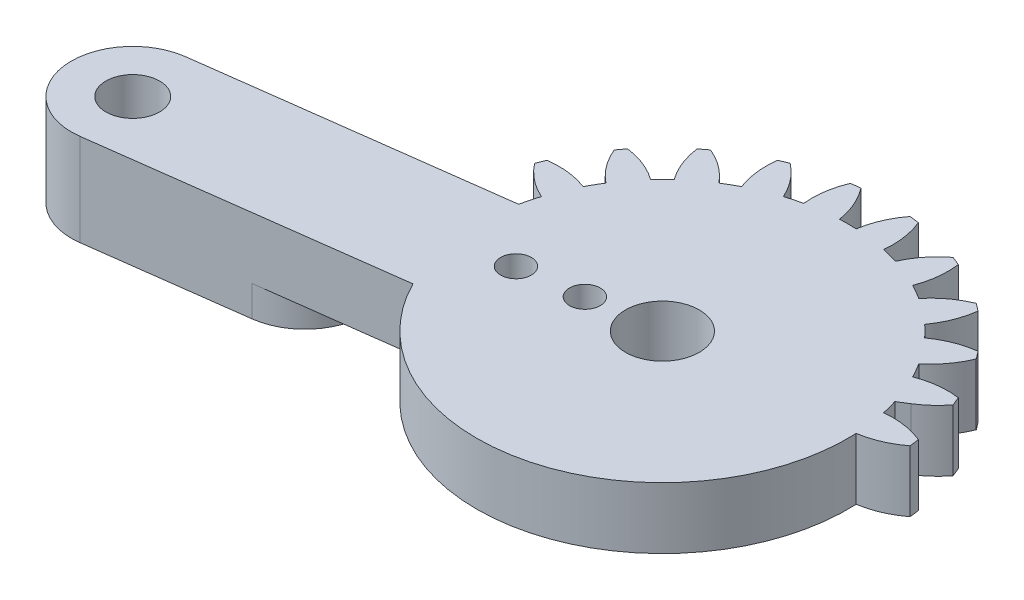
SolidWorks part; units mm, degrees
ref_plane "Front Plane" through (0, 0, 0) normal (0, 0, 1) x (1, 0, 0)
ref_plane "Top Plane" through (0, 0, 0) normal (0, 1, 0) x (1, 0, 0)
ref_plane "Right Plane" through (0, 0, 0) normal (1, 0, 0) x (0, 0, -1)
sketch "Sketch1" plane through (0, 0, 0) normal (0, 1, 0) x (1, 0, 0)
  line L0 (20.6437, 4) -> (2.0816, 4)
  line L1 (2.0816, -4) -> (20.6437, -4)
  arc A0 (2.0816, 4) -> (3.5217, 5.3071) centre (-0.7683, 8.5867) ccw
  arc A1 (3.5217, 5.3071) -> (3.2829, 5.8838) centre (-10.1063, 0) ccw
  arc A2 (3.2829, 5.8838) -> (0.6271, 5.5703) centre (2.5684, 0.5313) ccw
  arc A3 (0.6271, 5.5703) -> (0.0844, 6.5103) centre (-10.1063, 0) ccw
  arc A4 (0.0844, 6.5103) -> (1.6838, 8.6535) centre (-3.3089, 10.711) ccw
  arc A5 (1.6838, 8.6535) -> (1.3038, 9.1487) centre (-10.1063, 0) ccw
  arc A6 (1.3038, 9.1487) -> (-1.1803, 8.1585) centre (1.999, 3.7936) ccw
  arc A7 (-1.1803, 8.1585) -> (-1.9479, 8.926) centre (-10.1063, 0) ccw
  arc A8 (-1.9479, 8.926) -> (-0.9576, 11.4102) centre (-6.3127, 12.1053) ccw
  arc A9 (-0.9576, 11.4102) -> (-1.4528, 11.7901) centre (-10.1063, 0) ccw
  arc A10 (-1.4528, 11.7901) -> (-3.596, 10.1907) centre (0.6046, 6.7975) ccw
  arc A11 (-3.596, 10.1907) -> (-4.5361, 10.7334) centre (-10.1063, 0) ccw
  arc A12 (-4.5361, 10.7334) -> (-4.2225, 13.3892) centre (-9.5751, 12.6747) ccw
  arc A13 (-4.2225, 13.3892) -> (-4.7992, 13.6281) centre (-10.1063, 0) ccw
  arc A14 (-4.7992, 13.6281) -> (-6.4554, 11.5285) centre (-1.5196, 9.3381) ccw
  arc A15 (-6.4554, 11.5285) -> (-7.5039, 11.8094) centre (-10.1063, 0) ccw
  arc A16 (-7.5039, 11.8094) -> (-7.8884, 14.4558) centre (-12.8736, 12.3803) ccw
  arc A17 (-7.8884, 14.4558) -> (-8.5072, 14.5373) centre (-10.1063, 0) ccw
  arc A18 (-8.5072, 14.5373) -> (-9.5636, 12.0806) centre (-4.2291, 11.2423) ccw
  arc A19 (-9.5636, 12.0806) -> (-10.6491, 12.0806) centre (-10.1063, 0) ccw
  arc A20 (-10.6491, 12.0806) -> (-11.7054, 14.5373) centre (-15.9836, 11.2423) ccw
  arc A21 (-11.7054, 14.5373) -> (-12.3243, 14.4558) centre (-10.1063, 0) ccw
  arc A22 (-12.3243, 14.4558) -> (-12.7088, 11.8094) centre (-7.3391, 12.3803) ccw
  arc A23 (-12.7088, 11.8094) -> (-13.7573, 11.5285) centre (-10.1063, 0) ccw
  arc A24 (-13.7573, 11.5285) -> (-15.4135, 13.6281) centre (-18.6931, 9.3381) ccw
  arc A25 (-15.4135, 13.6281) -> (-15.9901, 13.3892) centre (-10.1063, 0) ccw
  arc A26 (-15.9901, 13.3892) -> (-15.6766, 10.7334) centre (-10.6376, 12.6747) ccw
  arc A27 (-15.6766, 10.7334) -> (-16.6166, 10.1907) centre (-10.1063, 0) ccw
  arc A28 (-16.6166, 10.1907) -> (-18.7599, 11.7901) centre (-20.8173, 6.7975) ccw
  arc A29 (-18.7599, 11.7901) -> (-19.255, 11.4102) centre (-10.1063, 0) ccw
  arc A30 (-19.255, 11.4102) -> (-18.2648, 8.926) centre (-13.9, 12.1053) ccw
  arc A31 (-18.2648, 8.926) -> (-19.0324, 8.1585) centre (-10.1063, 0) ccw
  arc A32 (-19.0324, 8.1585) -> (-21.5165, 9.1487) centre (-22.2117, 3.7936) ccw
  arc A33 (-21.5165, 9.1487) -> (-21.8965, 8.6535) centre (-10.1063, 0) ccw
  arc A34 (-21.8965, 8.6535) -> (-20.2971, 6.5103) centre (-16.9038, 10.711) ccw
  arc A35 (-20.2971, 6.5103) -> (-20.8398, 5.5703) centre (-10.1063, 0) ccw
  arc A36 (-20.8398, 5.5703) -> (-23.4956, 5.8838) centre (-22.7811, 0.5313) ccw
  arc A37 (-23.4956, 5.8838) -> (-23.7344, 5.3071) centre (-10.1063, 0) ccw
  arc A38 (-23.7344, 5.3071) -> (-21.6348, 3.6509) centre (-19.4444, 8.5867) ccw
  arc A39 (-21.6348, 3.6509) -> (-21.9157, 2.6025) centre (-10.1063, 0) ccw
  arc A40 (-21.9157, 2.6025) -> (-24.5622, 2.2179) centre (-22.4867, -2.7673) ccw
  arc A41 (-24.5622, 2.2179) -> (-24.6437, 1.5991) centre (-10.1063, 0) ccw
  arc A42 (-24.6437, 1.5991) -> (-22.1869, 0.5427) centre (-21.3486, 5.8773) ccw
  arc A43 (-22.1869, 0.5427) -> (-22.1869, -0.5427) centre (-10.1063, 0) ccw
  arc A44 (-22.1869, -0.5427) -> (-24.6437, -1.5991) centre (-21.3486, -5.8773) ccw
  arc A45 (-24.6437, -1.5991) -> (-24.5622, -2.2179) centre (-10.1063, 0) ccw
  arc A46 (-24.5622, -2.2179) -> (-21.9157, -2.6025) centre (-22.4867, 2.7673) ccw
  arc A47 (-21.9157, -2.6025) -> (-21.6348, -3.6509) centre (-10.1063, 0) ccw
  arc A48 (-21.6348, -3.6509) -> (-23.7344, -5.3071) centre (-19.4444, -8.5867) ccw
  arc A49 (-23.7344, -5.3071) -> (-23.4956, -5.8838) centre (-10.1063, 0) ccw
  arc A50 (-23.4956, -5.8838) -> (-20.8398, -5.5703) centre (-22.7811, -0.5313) ccw
  arc A51 (-20.8398, -5.5703) -> (-20.2971, -6.5103) centre (-10.1063, 0) ccw
  arc A52 (-20.2971, -6.5103) -> (-21.8965, -8.6535) centre (-16.9038, -10.711) ccw
  arc A53 (-21.8965, -8.6535) -> (-21.5165, -9.1487) centre (-10.1063, 0) ccw
  arc A54 (-21.5165, -9.1487) -> (-19.0324, -8.1585) centre (-22.2117, -3.7936) ccw
  arc A55 (-19.0324, -8.1585) -> (-18.2648, -8.926) centre (-10.1063, 0) ccw
  arc A56 (-18.2648, -8.926) -> (-19.255, -11.4102) centre (-13.9, -12.1053) ccw
  arc A57 (-19.255, -11.4102) -> (-18.7599, -11.7901) centre (-10.1063, 0) ccw
  arc A58 (-18.7599, -11.7901) -> (-16.6166, -10.1907) centre (-20.8173, -6.7975) ccw
  arc A59 (-16.6166, -10.1907) -> (-15.6766, -10.7334) centre (-10.1063, 0) ccw
  arc A60 (-15.6766, -10.7334) -> (-15.9901, -13.3892) centre (-10.6376, -12.6747) ccw
  arc A61 (-15.9901, -13.3892) -> (-15.4135, -13.6281) centre (-10.1063, 0) ccw
  arc A62 (-15.4135, -13.6281) -> (-13.7573, -11.5285) centre (-18.6931, -9.3381) ccw
  arc A63 (-13.7573, -11.5285) -> (-12.7088, -11.8094) centre (-10.1063, 0) ccw
  arc A64 (-12.7088, -11.8094) -> (-12.3243, -14.4558) centre (-7.3391, -12.3803) ccw
  arc A65 (-12.3243, -14.4558) -> (-11.7054, -14.5373) centre (-10.1063, 0) ccw
  arc A66 (-11.7054, -14.5373) -> (-10.6491, -12.0806) centre (-15.9836, -11.2423) ccw
  arc A67 (-10.6491, -12.0806) -> (-9.5636, -12.0806) centre (-10.1063, 0) ccw
  arc A68 (-9.5636, -12.0806) -> (-8.5072, -14.5373) centre (-4.2291, -11.2423) ccw
  arc A69 (-8.5072, -14.5373) -> (-7.8884, -14.4558) centre (-10.1063, 0) ccw
  arc A70 (-7.8884, -14.4558) -> (-7.5039, -11.8094) centre (-12.8736, -12.3803) ccw
  arc A71 (-7.5039, -11.8094) -> (-6.4554, -11.5285) centre (-10.1063, 0) ccw
  arc A72 (-6.4554, -11.5285) -> (-4.7992, -13.6281) centre (-1.5196, -9.3381) ccw
  arc A73 (-4.7992, -13.6281) -> (-4.2225, -13.3892) centre (-10.1063, 0) ccw
  arc A74 (-4.2225, -13.3892) -> (-4.5361, -10.7334) centre (-9.5751, -12.6747) ccw
  arc A75 (-4.5361, -10.7334) -> (-3.596, -10.1907) centre (-10.1063, 0) ccw
  arc A76 (-3.596, -10.1907) -> (-1.4528, -11.7901) centre (0.6046, -6.7975) ccw
  arc A77 (-1.4528, -11.7901) -> (-0.9576, -11.4102) centre (-10.1063, 0) ccw
  arc A78 (-0.9576, -11.4102) -> (-1.9479, -8.926) centre (-6.3127, -12.1053) ccw
  arc A79 (-1.9479, -8.926) -> (-1.1803, -8.1585) centre (-10.1063, 0) ccw
  arc A80 (-1.1803, -8.1585) -> (1.3038, -9.1487) centre (1.999, -3.7936) ccw
  arc A81 (1.3038, -9.1487) -> (1.6838, -8.6535) centre (-10.1063, 0) ccw
  arc A82 (1.6838, -8.6535) -> (0.0844, -6.5103) centre (-3.3089, -10.711) ccw
  arc A83 (0.0844, -6.5103) -> (0.6271, -5.5703) centre (-10.1063, 0) ccw
  arc A84 (0.6271, -5.5703) -> (3.2829, -5.8838) centre (2.5684, -0.5313) ccw
  arc A85 (3.2829, -5.8838) -> (3.5217, -5.3071) centre (-10.1063, 0) ccw
  arc A86 (3.5217, -5.3071) -> (2.0816, -4) centre (-0.7683, -8.5867) ccw
  arc A87 (20.6437, -4) -> (20.6437, 4) centre (20.6437, 0) ccw
  circle A88 centre (-10.1063, 0) radius 1.5
  circle A89 centre (20.6437, 0) radius 1.5
  dimension "D1" = 3
  dimension "D2" = 3
extrude "Boss-Extrude1" add sketch "Sketch1" along normal blind 4
sketch "Sketch3" plane through (0, 4, 0) normal (0, 1, 0) x (1, 0, 0)
  line L0 (-10.1063, 0) -> (-40.8563, 0) construction
  line L1 (-10.1063, 0) -> (-40.5933, -4.0137)
  line L2 (-10.6284, 3.9658) -> (-41.1154, -0.0479)
  line L3 (-9.5842, -3.9658) -> (-40.0712, -7.9795)
  line L4 (-10.1063, 0) -> (-4.5096, 13.5117) construction
  line L5 (-10.1063, 0) -> (-8.1974, 14.4999) construction
  circle A0 centre (-10.1063, 0) radius 1.5
  circle A1 centre (20.6437, 0) radius 1.5 construction
  circle A2 centre (20.6437, 0) radius 1.5
  circle A3 centre (-40.5933, -4.0137) radius 1.75
  circle A4 centre (-40.5933, -4.0137) radius 4
  circle A5 centre (-10.1063, 0) radius 4
  arc A6 (-4.2225, 13.3892) -> (-4.7992, 13.6281) centre (-10.1063, 0) ccw construction
  arc A7 (-7.8884, 14.4558) -> (-8.5072, 14.5373) centre (-10.1063, 0) ccw construction
  dimension "D2" = 3
  dimension "D5" = 3.5
  dimension "D6" = 8
  dimension "D7" = 8
  dimension "D1" = 30.75
  dimension "D4" = 7.5
extrude "Boss-Extrude2" add sketch "Sketch3" against normal blind 4
sketch "Sketch4" plane through (0, 4, 0) normal (0, 1, 0) x (1, 0, 0)
  line L0 (20.6437, 4) -> (2.0816, 4) construction
  line L1 (2.0816, -4) -> (20.6437, -4) construction
  line L2 (20.6437, 4) -> (2.0816, 4)
  line L3 (2.0816, -4) -> (20.6437, -4)
  line L4 (2.0816, 4) -> (1.4381, 3.6001)
  line L5 (-21.6245, -5.5509) -> (-20.8986, -5.4553)
  line L6 (-10.1063, 0) -> (0.0844, 6.5103) construction
  line L7 (-10.1063, 0) -> (1.9742, 0.5427) construction
  line L8 (-24.5755, 2.1296) -> (-41.1154, -0.0479)
  line L9 (-40.0712, -7.9795) -> (-23.5312, -5.8019)
  line L10 (2.0816, -4) -> (20.6437, -4)
  line L11 (20.6437, 4) -> (2.0816, 4)
  line L12 (-21.9429, 2.4762) -> (-41.1154, -0.0479)
  line L13 (-40.0712, -7.9795) -> (-21.6245, -5.5509)
  line L14 (2.0816, -4) -> (20.6437, -4)
  line L15 (20.6437, 4) -> (2.0816, 4)
  circle A0 centre (-10.1063, 0) radius 12.0927
  arc A1 (3.2829, 5.8838) -> (0.6271, 5.5703) centre (2.5684, 0.5313) ccw construction
  arc A2 (3.5217, 5.3071) -> (3.2829, 5.8838) centre (-10.1063, 0) ccw construction
  arc A3 (2.0816, 4) -> (3.5217, 5.3071) centre (-0.7683, 8.5867) ccw construction
  arc A4 (20.6437, -4) -> (20.6437, 4) centre (20.6437, 0) ccw construction
  arc A5 (3.5217, -5.3071) -> (2.0816, -4) centre (-0.7683, -8.5867) ccw construction
  arc A6 (3.2829, -5.8838) -> (3.5217, -5.3071) centre (-10.1063, 0) ccw construction
  arc A7 (0.6271, -5.5703) -> (3.2829, -5.8838) centre (2.5684, -0.5313) ccw construction
  arc A8 (3.2829, 5.8838) -> (0.6271, 5.5703) centre (2.5684, 0.5313) ccw
  arc A9 (3.5217, 5.3071) -> (3.2829, 5.8838) centre (-10.1063, 0) ccw
  arc A10 (2.0816, 4) -> (3.5217, 5.3071) centre (-0.7683, 8.5867) ccw
  arc A11 (20.6437, -4) -> (20.6437, 4) centre (20.6437, 0) ccw
  arc A12 (3.5217, -5.3071) -> (2.0816, -4) centre (-0.7683, -8.5867) ccw
  arc A13 (3.2829, -5.8838) -> (3.5217, -5.3071) centre (-10.1063, 0) ccw
  arc A14 (0.6271, -5.5703) -> (3.2829, -5.8838) centre (2.5684, -0.5313) ccw
  arc A15 (1.9742, 0.5427) -> (4.431, 1.5991) centre (1.1359, 5.8773) ccw
  arc A16 (4.3495, 2.2179) -> (1.7031, 2.6025) centre (2.274, -2.7673) ccw
  arc A17 (4.431, 1.5991) -> (4.3495, 2.2179) centre (-10.1063, 0) ccw
  arc A95 (-21.6348, 3.6509) -> (-21.9157, 2.6025) centre (-10.1063, 0) ccw
  arc A96 (-41.1154, -0.0479) -> (-40.0712, -7.9795) centre (-40.5933, -4.0137) ccw
  arc A97 (-20.2971, -6.5103) -> (-21.8965, -8.6535) centre (-16.9038, -10.711) ccw
  arc A98 (-21.8965, -8.6535) -> (-21.5165, -9.1487) centre (-10.1063, 0) ccw
  arc A99 (-21.5165, -9.1487) -> (-19.0324, -8.1585) centre (-22.2117, -3.7936) ccw
  arc A100 (-19.0324, -8.1585) -> (-18.2648, -8.926) centre (-10.1063, 0) ccw
  arc A101 (-18.2648, -8.926) -> (-19.255, -11.4102) centre (-13.9, -12.1053) ccw
  arc A102 (-19.255, -11.4102) -> (-18.7599, -11.7901) centre (-10.1063, 0) ccw
  arc A103 (-18.7599, -11.7901) -> (-16.6166, -10.1907) centre (-20.8173, -6.7975) ccw
  arc A104 (-16.6166, -10.1907) -> (-15.6766, -10.7334) centre (-10.1063, 0) ccw
  arc A105 (-15.6766, -10.7334) -> (-15.9901, -13.3892) centre (-10.6376, -12.6747) ccw
  arc A106 (-15.9901, -13.3892) -> (-15.4135, -13.6281) centre (-10.1063, 0) ccw
  arc A107 (-15.4135, -13.6281) -> (-13.7573, -11.5285) centre (-18.6931, -9.3381) ccw
  arc A108 (-13.7573, -11.5285) -> (-12.7088, -11.8094) centre (-10.1063, 0) ccw
  arc A109 (-12.7088, -11.8094) -> (-12.3243, -14.4558) centre (-7.3391, -12.3803) ccw
  arc A110 (-12.3243, -14.4558) -> (-11.7054, -14.5373) centre (-10.1063, 0) ccw
  arc A111 (-11.7054, -14.5373) -> (-10.6491, -12.0806) centre (-15.9836, -11.2423) ccw
  arc A112 (-10.6491, -12.0806) -> (-9.5636, -12.0806) centre (-10.1063, 0) ccw
  arc A113 (-9.5636, -12.0806) -> (-8.5072, -14.5373) centre (-4.2291, -11.2423) ccw
  arc A114 (-8.5072, -14.5373) -> (-7.8884, -14.4558) centre (-10.1063, 0) ccw
  arc A115 (-7.8884, -14.4558) -> (-7.5039, -11.8094) centre (-12.8736, -12.3803) ccw
  arc A116 (-7.5039, -11.8094) -> (-6.4554, -11.5285) centre (-10.1063, 0) ccw
  arc A117 (-6.4554, -11.5285) -> (-4.7992, -13.6281) centre (-1.5196, -9.3381) ccw
  arc A118 (-4.7992, -13.6281) -> (-4.2225, -13.3892) centre (-10.1063, 0) ccw
  arc A119 (-4.2225, -13.3892) -> (-4.5361, -10.7334) centre (-9.5751, -12.6747) ccw
  arc A120 (-4.5361, -10.7334) -> (-3.596, -10.1907) centre (-10.1063, 0) ccw
  arc A121 (-3.596, -10.1907) -> (-1.4528, -11.7901) centre (0.6046, -6.7975) ccw
  arc A122 (-1.4528, -11.7901) -> (-0.9576, -11.4102) centre (-10.1063, 0) ccw
  arc A123 (-0.9576, -11.4102) -> (-1.9479, -8.926) centre (-6.3127, -12.1053) ccw
  arc A124 (-1.9479, -8.926) -> (-1.1803, -8.1585) centre (-10.1063, 0) ccw
  arc A125 (-1.1803, -8.1585) -> (1.3038, -9.1487) centre (1.999, -3.7936) ccw
  arc A126 (1.3038, -9.1487) -> (1.6838, -8.6535) centre (-10.1063, 0) ccw
  arc A127 (1.6838, -8.6535) -> (0.0844, -6.5103) centre (-3.3089, -10.711) ccw
  arc A128 (0.0844, -6.5103) -> (0.6271, -5.5703) centre (-10.1063, 0) ccw
  arc A129 (0.6271, -5.5703) -> (3.2829, -5.8838) centre (2.5684, -0.5313) ccw
  arc A130 (3.2829, -5.8838) -> (3.5217, -5.3071) centre (-10.1063, 0) ccw
  arc A131 (3.5217, -5.3071) -> (2.0816, -4) centre (-0.7683, -8.5867) ccw
  arc A132 (20.6437, -4) -> (20.6437, 4) centre (20.6437, 0) ccw
  arc A133 (2.0816, 4) -> (3.5217, 5.3071) centre (-0.7683, 8.5867) ccw
  arc A134 (3.5217, 5.3071) -> (3.2829, 5.8838) centre (-10.1063, 0) ccw
  arc A135 (3.2829, 5.8838) -> (0.6271, 5.5703) centre (2.5684, 0.5313) ccw
  arc A136 (0.6271, 5.5703) -> (0.0844, 6.5103) centre (-10.1063, 0) ccw
  arc A137 (0.0844, 6.5103) -> (1.6838, 8.6535) centre (-3.3089, 10.711) ccw
  arc A138 (1.6838, 8.6535) -> (1.3038, 9.1487) centre (-10.1063, 0) ccw
  arc A139 (1.3038, 9.1487) -> (-1.1803, 8.1585) centre (1.999, 3.7936) ccw
  arc A140 (-1.1803, 8.1585) -> (-1.9479, 8.926) centre (-10.1063, 0) ccw
  arc A141 (-1.9479, 8.926) -> (-0.9576, 11.4102) centre (-6.3127, 12.1053) ccw
  arc A142 (-0.9576, 11.4102) -> (-1.4528, 11.7901) centre (-10.1063, 0) ccw
  arc A143 (-1.4528, 11.7901) -> (-3.596, 10.1907) centre (0.6046, 6.7975) ccw
  arc A144 (-3.596, 10.1907) -> (-4.5361, 10.7334) centre (-10.1063, 0) ccw
  arc A145 (-4.5361, 10.7334) -> (-4.2225, 13.3892) centre (-9.5751, 12.6747) ccw
  arc A146 (-4.2225, 13.3892) -> (-4.7992, 13.6281) centre (-10.1063, 0) ccw
  arc A147 (-4.7992, 13.6281) -> (-6.4554, 11.5285) centre (-1.5196, 9.3381) ccw
  arc A148 (-6.4554, 11.5285) -> (-7.5039, 11.8094) centre (-10.1063, 0) ccw
  arc A149 (-7.5039, 11.8094) -> (-7.8884, 14.4558) centre (-12.8736, 12.3803) ccw
  arc A150 (-7.8884, 14.4558) -> (-8.5072, 14.5373) centre (-10.1063, 0) ccw
  arc A151 (-8.5072, 14.5373) -> (-9.5636, 12.0806) centre (-4.2291, 11.2423) ccw
  arc A152 (-9.5636, 12.0806) -> (-10.6491, 12.0806) centre (-10.1063, 0) ccw
  arc A153 (-10.6491, 12.0806) -> (-11.7054, 14.5373) centre (-15.9836, 11.2423) ccw
  arc A154 (-11.7054, 14.5373) -> (-12.3243, 14.4558) centre (-10.1063, 0) ccw
  arc A155 (-12.3243, 14.4558) -> (-12.7088, 11.8094) centre (-7.3391, 12.3803) ccw
  arc A156 (-12.7088, 11.8094) -> (-13.7573, 11.5285) centre (-10.1063, 0) ccw
  arc A157 (-13.7573, 11.5285) -> (-15.4135, 13.6281) centre (-18.6931, 9.3381) ccw
  arc A158 (-15.4135, 13.6281) -> (-15.9901, 13.3892) centre (-10.1063, 0) ccw
  arc A159 (-15.9901, 13.3892) -> (-15.6766, 10.7334) centre (-10.6376, 12.6747) ccw
  arc A160 (-15.6766, 10.7334) -> (-16.6166, 10.1907) centre (-10.1063, 0) ccw
  arc A161 (-16.6166, 10.1907) -> (-18.7599, 11.7901) centre (-20.8173, 6.7975) ccw
  arc A162 (-18.7599, 11.7901) -> (-19.255, 11.4102) centre (-10.1063, 0) ccw
  arc A163 (-19.255, 11.4102) -> (-18.2648, 8.926) centre (-13.9, 12.1053) ccw
  arc A164 (-18.2648, 8.926) -> (-19.0324, 8.1585) centre (-10.1063, 0) ccw
  arc A165 (-19.0324, 8.1585) -> (-21.5165, 9.1487) centre (-22.2117, 3.7936) ccw
  arc A166 (-21.5165, 9.1487) -> (-21.8965, 8.6535) centre (-10.1063, 0) ccw
  arc A167 (-21.8965, 8.6535) -> (-20.2971, 6.5103) centre (-16.9038, 10.711) ccw
  arc A168 (-20.2971, 6.5103) -> (-20.8398, 5.5703) centre (-10.1063, 0) ccw
  arc A169 (-20.8398, 5.5703) -> (-23.4956, 5.8838) centre (-22.7811, 0.5313) ccw
  arc A170 (-23.4956, 5.8838) -> (-23.7344, 5.3071) centre (-10.1063, 0) ccw
  arc A171 (-23.7344, 5.3071) -> (-21.6348, 3.6509) centre (-19.4444, 8.5867) ccw
  arc A172 (-21.6348, 3.6509) -> (-21.9157, 2.6025) centre (-10.1063, 0) ccw
  arc A175 (-23.4956, -5.8838) -> (-20.8398, -5.5703) centre (-22.7811, -0.5313) ccw
  arc A176 (-41.1154, -0.0479) -> (-40.0712, -7.9795) centre (-40.5933, -4.0137) ccw
  arc A177 (-20.2971, -6.5103) -> (-21.8965, -8.6535) centre (-16.9038, -10.711) ccw
  arc A178 (-21.8965, -8.6535) -> (-21.5165, -9.1487) centre (-10.1063, 0) ccw
  arc A179 (-21.5165, -9.1487) -> (-19.0324, -8.1585) centre (-22.2117, -3.7936) ccw
  arc A180 (-19.0324, -8.1585) -> (-18.2648, -8.926) centre (-10.1063, 0) ccw
  arc A181 (-18.2648, -8.926) -> (-19.255, -11.4102) centre (-13.9, -12.1053) ccw
  arc A182 (-19.255, -11.4102) -> (-18.7599, -11.7901) centre (-10.1063, 0) ccw
  arc A183 (-18.7599, -11.7901) -> (-16.6166, -10.1907) centre (-20.8173, -6.7975) ccw
  arc A184 (-16.6166, -10.1907) -> (-15.6766, -10.7334) centre (-10.1063, 0) ccw
  arc A185 (-15.6766, -10.7334) -> (-15.9901, -13.3892) centre (-10.6376, -12.6747) ccw
  arc A186 (-15.9901, -13.3892) -> (-15.4135, -13.6281) centre (-10.1063, 0) ccw
  arc A187 (-15.4135, -13.6281) -> (-13.7573, -11.5285) centre (-18.6931, -9.3381) ccw
  arc A188 (-13.7573, -11.5285) -> (-12.7088, -11.8094) centre (-10.1063, 0) ccw
  arc A189 (-12.7088, -11.8094) -> (-12.3243, -14.4558) centre (-7.3391, -12.3803) ccw
  arc A190 (-12.3243, -14.4558) -> (-11.7054, -14.5373) centre (-10.1063, 0) ccw
  arc A191 (-11.7054, -14.5373) -> (-10.6491, -12.0806) centre (-15.9836, -11.2423) ccw
  arc A192 (-10.6491, -12.0806) -> (-9.5636, -12.0806) centre (-10.1063, 0) ccw
  arc A193 (-9.5636, -12.0806) -> (-8.5072, -14.5373) centre (-4.2291, -11.2423) ccw
  arc A194 (-8.5072, -14.5373) -> (-7.8884, -14.4558) centre (-10.1063, 0) ccw
  arc A195 (-7.8884, -14.4558) -> (-7.5039, -11.8094) centre (-12.8736, -12.3803) ccw
  arc A196 (-7.5039, -11.8094) -> (-6.4554, -11.5285) centre (-10.1063, 0) ccw
  arc A197 (-6.4554, -11.5285) -> (-4.7992, -13.6281) centre (-1.5196, -9.3381) ccw
  arc A198 (-4.7992, -13.6281) -> (-4.2225, -13.3892) centre (-10.1063, 0) ccw
  arc A199 (-4.2225, -13.3892) -> (-4.5361, -10.7334) centre (-9.5751, -12.6747) ccw
  arc A200 (-4.5361, -10.7334) -> (-3.596, -10.1907) centre (-10.1063, 0) ccw
  arc A201 (-3.596, -10.1907) -> (-1.4528, -11.7901) centre (0.6046, -6.7975) ccw
  arc A202 (-1.4528, -11.7901) -> (-0.9576, -11.4102) centre (-10.1063, 0) ccw
  arc A203 (-0.9576, -11.4102) -> (-1.9479, -8.926) centre (-6.3127, -12.1053) ccw
  arc A204 (-1.9479, -8.926) -> (-1.1803, -8.1585) centre (-10.1063, 0) ccw
  arc A205 (-1.1803, -8.1585) -> (1.3038, -9.1487) centre (1.999, -3.7936) ccw
  arc A206 (1.3038, -9.1487) -> (1.6838, -8.6535) centre (-10.1063, 0) ccw
  arc A207 (1.6838, -8.6535) -> (0.0844, -6.5103) centre (-3.3089, -10.711) ccw
  arc A208 (0.0844, -6.5103) -> (0.6271, -5.5703) centre (-10.1063, 0) ccw
  arc A209 (0.6271, -5.5703) -> (3.2829, -5.8838) centre (2.5684, -0.5313) ccw
  arc A210 (3.2829, -5.8838) -> (3.5217, -5.3071) centre (-10.1063, 0) ccw
  arc A211 (3.5217, -5.3071) -> (2.0816, -4) centre (-0.7683, -8.5867) ccw
  arc A212 (20.6437, -4) -> (20.6437, 4) centre (20.6437, 0) ccw
  arc A213 (2.0816, 4) -> (3.5217, 5.3071) centre (-0.7683, 8.5867) ccw
  arc A214 (3.5217, 5.3071) -> (3.2829, 5.8838) centre (-10.1063, 0) ccw
  arc A215 (3.2829, 5.8838) -> (0.6271, 5.5703) centre (2.5684, 0.5313) ccw
  arc A216 (0.6271, 5.5703) -> (0.0844, 6.5103) centre (-10.1063, 0) ccw
  arc A217 (0.0844, 6.5103) -> (1.6838, 8.6535) centre (-3.3089, 10.711) ccw
  arc A218 (1.6838, 8.6535) -> (1.3038, 9.1487) centre (-10.1063, 0) ccw
  arc A219 (1.3038, 9.1487) -> (-1.1803, 8.1585) centre (1.999, 3.7936) ccw
  arc A220 (-1.1803, 8.1585) -> (-1.9479, 8.926) centre (-10.1063, 0) ccw
  arc A221 (-1.9479, 8.926) -> (-0.9576, 11.4102) centre (-6.3127, 12.1053) ccw
  arc A222 (-0.9576, 11.4102) -> (-1.4528, 11.7901) centre (-10.1063, 0) ccw
  arc A223 (-1.4528, 11.7901) -> (-3.596, 10.1907) centre (0.6046, 6.7975) ccw
  arc A224 (-3.596, 10.1907) -> (-4.5361, 10.7334) centre (-10.1063, 0) ccw
  arc A225 (-4.5361, 10.7334) -> (-4.2225, 13.3892) centre (-9.5751, 12.6747) ccw
  arc A226 (-4.2225, 13.3892) -> (-4.7992, 13.6281) centre (-10.1063, 0) ccw
  arc A227 (-4.7992, 13.6281) -> (-6.4554, 11.5285) centre (-1.5196, 9.3381) ccw
  arc A228 (-6.4554, 11.5285) -> (-7.5039, 11.8094) centre (-10.1063, 0) ccw
  arc A229 (-7.5039, 11.8094) -> (-7.8884, 14.4558) centre (-12.8736, 12.3803) ccw
  arc A230 (-7.8884, 14.4558) -> (-8.5072, 14.5373) centre (-10.1063, 0) ccw
  arc A231 (-8.5072, 14.5373) -> (-9.5636, 12.0806) centre (-4.2291, 11.2423) ccw
  arc A232 (-9.5636, 12.0806) -> (-10.6491, 12.0806) centre (-10.1063, 0) ccw
  arc A233 (-10.6491, 12.0806) -> (-11.7054, 14.5373) centre (-15.9836, 11.2423) ccw
  arc A234 (-11.7054, 14.5373) -> (-12.3243, 14.4558) centre (-10.1063, 0) ccw
  arc A235 (-12.3243, 14.4558) -> (-12.7088, 11.8094) centre (-7.3391, 12.3803) ccw
  arc A236 (-12.7088, 11.8094) -> (-13.7573, 11.5285) centre (-10.1063, 0) ccw
  arc A237 (-13.7573, 11.5285) -> (-15.4135, 13.6281) centre (-18.6931, 9.3381) ccw
  arc A238 (-15.4135, 13.6281) -> (-15.9901, 13.3892) centre (-10.1063, 0) ccw
  arc A239 (-15.9901, 13.3892) -> (-15.6766, 10.7334) centre (-10.6376, 12.6747) ccw
  arc A240 (-15.6766, 10.7334) -> (-16.6166, 10.1907) centre (-10.1063, 0) ccw
  arc A241 (-16.6166, 10.1907) -> (-18.7599, 11.7901) centre (-20.8173, 6.7975) ccw
  arc A242 (-18.7599, 11.7901) -> (-19.255, 11.4102) centre (-10.1063, 0) ccw
  arc A243 (-19.255, 11.4102) -> (-18.2648, 8.926) centre (-13.9, 12.1053) ccw
  arc A244 (-18.2648, 8.926) -> (-19.0324, 8.1585) centre (-10.1063, 0) ccw
  arc A245 (-19.0324, 8.1585) -> (-21.5165, 9.1487) centre (-22.2117, 3.7936) ccw
  arc A246 (-21.5165, 9.1487) -> (-21.8965, 8.6535) centre (-10.1063, 0) ccw
  arc A247 (-21.8965, 8.6535) -> (-20.2971, 6.5103) centre (-16.9038, 10.711) ccw
  arc A248 (-20.2971, 6.5103) -> (-20.8398, 5.5703) centre (-10.1063, 0) ccw
  arc A249 (-20.8398, 5.5703) -> (-23.4956, 5.8838) centre (-22.7811, 0.5313) ccw
  arc A250 (-23.4956, 5.8838) -> (-23.7344, 5.3071) centre (-10.1063, 0) ccw
  arc A251 (-23.7344, 5.3071) -> (-21.6348, 3.6509) centre (-19.4444, 8.5867) ccw
  arc A252 (-23.4956, -5.8838) -> (-20.8398, -5.5703) centre (-22.7811, -0.5313) ccw
  arc A253 (-20.8398, -5.5703) -> (-20.2971, -6.5103) centre (-10.1063, 0) ccw
  arc A254 (-20.8398, -5.5703) -> (-20.2971, -6.5103) centre (-10.1063, 0) ccw
  arc A255 (-23.5312, -5.8019) -> (-23.4956, -5.8838) centre (-10.1063, 0) ccw
  arc A256 (-23.5312, -5.8019) -> (-23.4956, -5.8838) centre (-10.1063, 0) ccw
  arc A257 (-21.9157, 2.6025) -> (-24.5622, 2.2179) centre (-22.4867, -2.7673) ccw
  arc A258 (-21.9157, 2.6025) -> (-24.5622, 2.2179) centre (-22.4867, -2.7673) ccw
  arc A259 (-24.5622, 2.2179) -> (-24.5755, 2.1296) centre (-10.1063, 0) ccw
  arc A260 (-24.5622, 2.2179) -> (-24.5755, 2.1296) centre (-10.1063, 0) ccw
  point P40 (-10.1063, 0)
  dimension "D2" = 24.1855
  dimension "D4" = 30
  dimension "D1" = 0
  dimension "D3" = 2
extrude "Cut-Extrude1" cut sketch "Sketch4" against normal blind 4 contours A178 A179 A0 L5 A177 | A182 A183 A0 A181 | A186 A187 A0 A185 | A190 A191 A0 A189 | A194 A195 A0 A193 | A198 A199 A0 A197 | A202 A203 A0 A201 | A206 A207 A0 A205 | A258 A260 L12 A0 | L13 A256 A252 A0 L5 | A0 A14 A13 A12 L3 A11 L2 L4
sketch "Sketch5" plane through (0, 4, 0) normal (0, 1, 0) x (1, 0, 0)
  line L0 (-10.1063, 0) -> (-40.5933, -4.0137) construction
  circle A0 centre (-10.1063, 0) radius 2.4
  circle A2 centre (-14.5678, -0.5874) radius 1
  circle A4 centre (-18.5336, -1.1095) radius 1
  dimension "D1" = 4.8
  dimension "D2" = 4.5
  dimension "D3" = 2
  dimension "D4" = 2
  dimension "D5" = 4
extrude "Cut-Extrude2" cut sketch "Sketch5" against normal up to next
sketch "Sketch7" plane through (0, 4, 0) normal (0, 1, 0) x (1, 0, 0)
  circle A0 centre (-10.1063, 0) radius 13.45 construction
  circle A1 centre (-10.1063, 0) radius 13.45
sketch "Sketch8" plane through (0, 0, 0) normal (0, -1, 0) x (1, 0, 0)
  line L0 (-30.6788, 2.7084) -> (-40.5933, 4.0137) construction
  line L1 (-20.8986, 5.4553) -> (-40.0712, 7.9795) construction
  line L2 (-30.1567, 6.6742) -> (-40.0712, 7.9795)
  line L3 (-21.9429, -2.4762) -> (-41.1154, 0.0479) construction
  line L4 (-31.2009, -1.2574) -> (-41.1154, 0.0479)
  arc A0 (-31.2009, -1.2574) -> (-30.1567, 6.6742) centre (-30.6788, 2.7084) ccw
  arc A1 (-40.0712, 7.9795) -> (-41.1154, 0.0479) centre (-40.5933, 4.0137) ccw construction
  arc A2 (-40.0712, 7.9795) -> (-41.1154, 0.0479) centre (-40.5933, 4.0137) ccw
  circle A3 centre (-40.5933, 4.0137) radius 1.75 construction
  circle A4 centre (-40.5933, 4.0137) radius 1.75
  dimension "D1" = 10
extrude "Boss-Extrude3" add sketch "Sketch8" along normal blind 2
